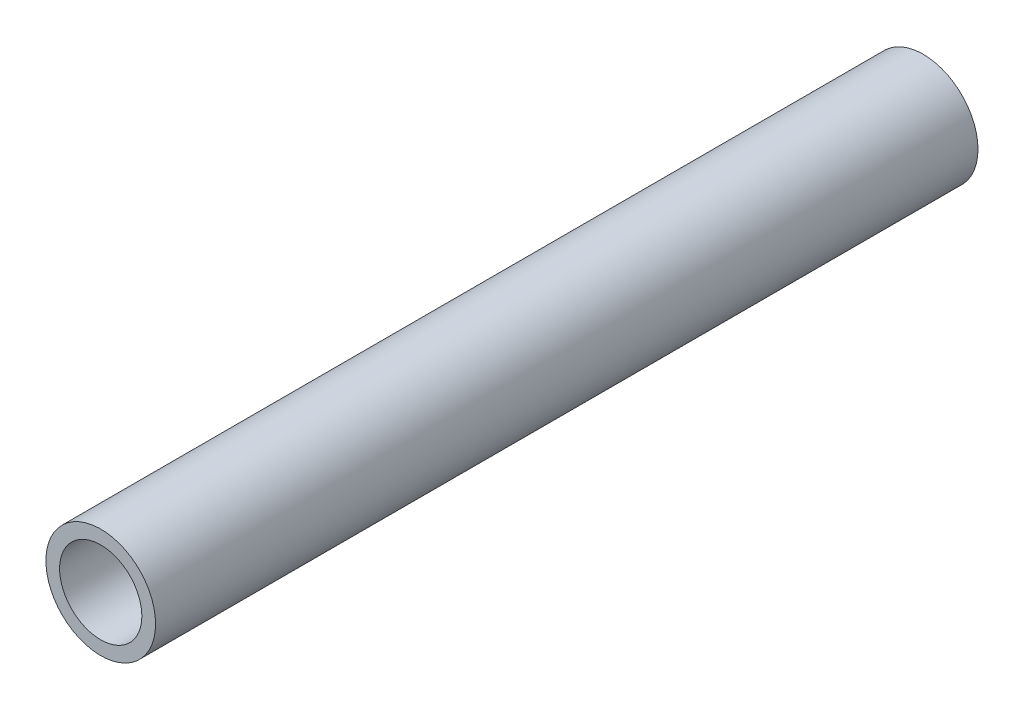
SolidWorks part; units mm, degrees
ref_plane "Plan de face" through (0, 0, 0) normal (0, 0, 1) x (1, 0, 0)
ref_plane "Plan de dessus" through (0, 0, 0) normal (0, 1, 0) x (1, 0, 0)
ref_plane "Plan de droite" through (0, 0, 0) normal (1, 0, 0) x (0, 0, -1)
sketch "Esquisse1" plane through (0, 0, 0) normal (0, 0, 1) x (1, 0, 0)
  circle A0 centre (0, 0) radius 4
  dimension "D1" = 8
extrude "Boss.-Extru.1" add sketch "Esquisse1" along normal blind 60
sketch "Esquisse2" plane through (0, 0, 60) normal (0, 0, 1) x (1, 0, 0)
  circle A0 centre (0, 0) radius 3
  dimension "D1" = 6
extrude "Enlèv. mat.-Extru.1" cut sketch "Esquisse2" against normal blind 5
